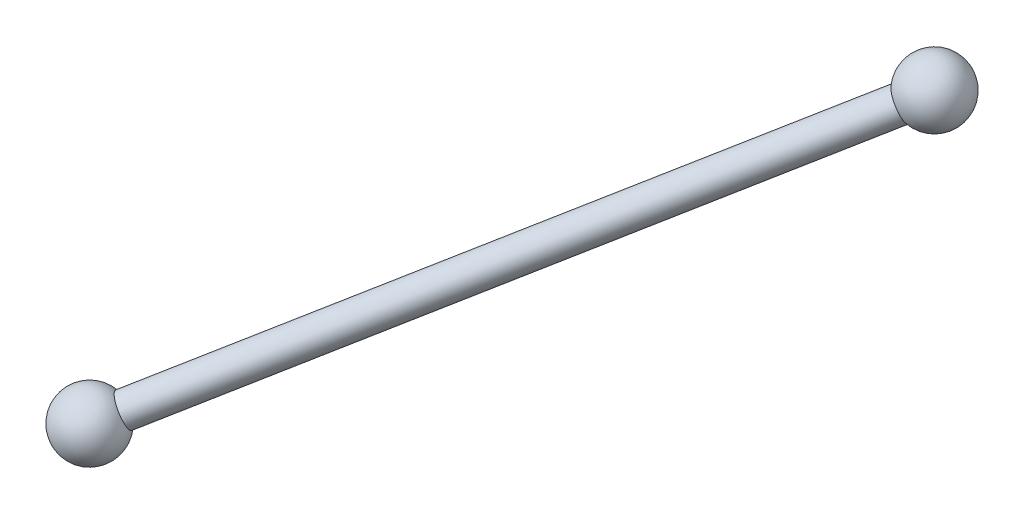
SolidWorks part; units mm, degrees
other "Compression Inner Strut Lane2"
other "Compression Inner Strut Lane2 Left"
ref_plane "Front Plane" through (0, 0, 0) normal (0, 0, 1) x (1, 0, 0)
ref_plane "Top Plane" through (0, 0, 0) normal (0, 1, 0) x (1, 0, 0)
ref_plane "Right Plane" through (0, 0, 0) normal (1, 0, 0) x (0, 0, -1)
sketch3d "Straight strut core sketch datum points"
  point P0 (-71.2917, -73, 25.9808)
  point P1 (-63.5805, -69.4081, 31.2378)
  point P2 (-71.2917, -81.2568, 31.6222)
ref_plane "Straight strut core sketch plane" through (-19.2131, 13.1273, 19.2131) normal (0.6367, -0.435, -0.6367) x (-0.7711, -0.3592, -0.5257)
sketch "Straight strut core sketch" plane through (-19.2131, 13.1273, 19.2131) normal (0.6367, -0.435, -0.6367) x (-0.7711, -0.3592, -0.5257)
  circle A0 centre (67.5366, -74.9313) radius 1.5
extrude "Straight strut core" add sketch "Straight strut core sketch" along normal blind 64.3649 separate body
sketch3d "Ball end1 axis line"
  line L0 (-71.2917, -73, 15.9808) -> (-71.2917, -73, 35.9808) construction
ref_axis "Ball end1 axis" through (-71.2917, -73, 15.9808) along (0, 0, 1)
sketch3d "Ball end1 profile datum points"
  point P0 (-71.2917, -73, 25.9808)
  point P1 (-61.2917, -73, 25.9808)
  point P2 (-71.2917, -73, 35.9808)
ref_plane "Ball end1 profile plane" through (0, -73, 0) normal (0, -1, 0) x (-1, 0, 0)
sketch "Ball end1 profile" plane through (0, -73, 0) normal (0, -1, 0) x (-1, 0, 0)
  line L0 (71.2917, -28.9808) -> (71.2917, -22.9808)
  arc A0 (71.2917, -22.9808) -> (71.2917, -28.9808) centre (71.2917, -25.9808) ccw
revolve "Ball end1" add sketch "Ball end1 profile" angle 360 about axis through (-71.2917, -73, 15.9808) along (0, 0, 1)
sketch3d "Ball end2 axis line"
  line L0 (-30.3109, -101, -25) -> (-30.3109, -101, -5) construction
ref_axis "Ball end2 axis" through (-30.3109, -101, -25) along (0, 0, 1)
sketch3d "Ball end2 profile datum points"
  point P0 (-30.3109, -101, -15)
  point P1 (-20.3109, -101, -15)
  point P2 (-30.3109, -101, -5)
ref_plane "Ball end2 profile plane" through (0, -101, 0) normal (0, -1, 0) x (-1, 0, 0)
sketch "Ball end2 profile" plane through (0, -101, 0) normal (0, -1, 0) x (-1, 0, 0)
  line L0 (30.3109, 12) -> (30.3109, 18)
  arc A0 (30.3109, 18) -> (30.3109, 12) centre (30.3109, 15) ccw
revolve "Ball end2" add sketch "Ball end2 profile" angle 360 about axis through (-30.3109, -101, -25) along (0, 0, 1)
sketch3d "Mirror1 profile datum points"
  point P0 (0, 0, 0)
  point P1 (10, 0, 0)
  point P2 (0, 0, 10)
ref_plane "Mirror1 profile plane" through (0, 0, 0) normal (0, -1, 0) x (-1, 0, 0)
mirror "Mirror1" about plane through (0, 0, 0) normal (0, -1, 0) of bodies 103
delete or keep bodies "Remove1" type delete bodies bodies 103
